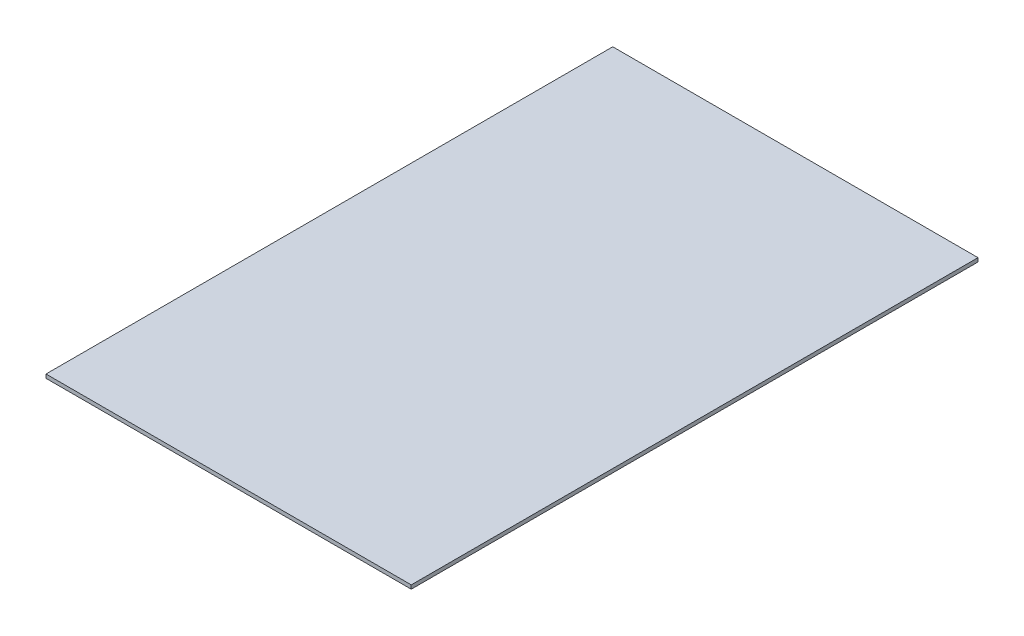
SolidWorks part; units mm, degrees
material "ABS PC"
ref_plane "Front Plane" through (0, 0, 0) normal (0, 0, 1) x (1, 0, 0)
ref_plane "Top Plane" through (0, 0, 0) normal (0, 1, 0) x (1, 0, 0)
ref_plane "Right Plane" through (0, 0, 0) normal (1, 0, 0) x (0, 0, -1)
sketch "Sketch1" plane through (0, 0, 0) normal (0, 1, 0) x (1, 0, 0)
  line L1 (0, 0) -> (580, 0)
  line L2 (0, 0) -> (0, 900)
  line L3 (0, 900) -> (580, 900)
  line L4 (580, 0) -> (580, 900)
  dimension "D1" = 900
  dimension "D2" = 580
extrude "Boss-Extrude1" add sketch "Sketch1" along normal blind 6
